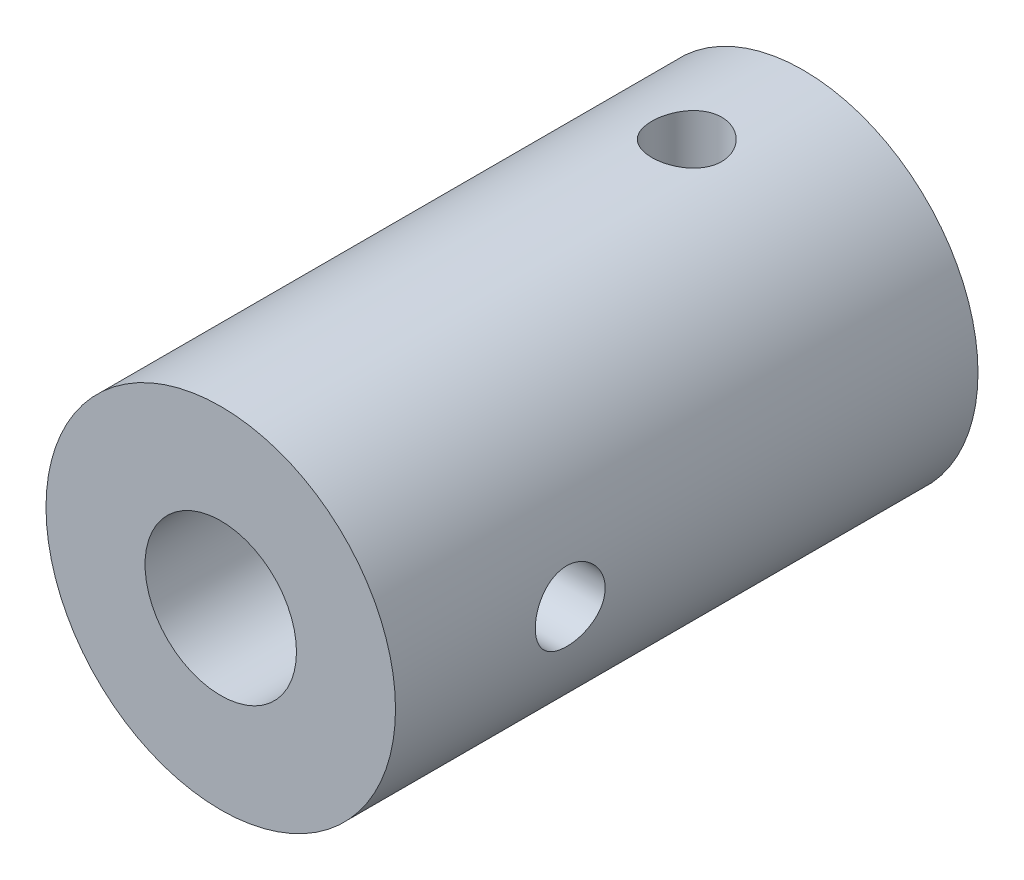
SolidWorks part; units mm, degrees
ref_plane "Front Plane" through (0, 0, 0) normal (0, 0, 1) x (1, 0, 0)
ref_plane "Top Plane" through (0, 0, 0) normal (0, 1, 0) x (1, 0, 0)
ref_plane "Right Plane" through (0, 0, 0) normal (1, 0, 0) x (0, 0, -1)
sketch "Sketch3" plane through (0, 0, 0) normal (0, 0, 1) x (1, 0, 0)
  circle A0 centre (0, 0) radius 7.5
  circle A1 centre (0, 0) radius 3.25
  dimension "D1" = 6.5
  dimension "D2" = 15
extrude "Boss-Extrude1" add sketch "Sketch3" along normal mid plane 25
sketch "Sketch4" plane through (0, 0, 0) normal (1, 0, 0) x (0, 0, -1)
  line L0 (-12.5, 7.5) -> (-12.5, -7.5) construction
  line L1 (12.5, -7.5) -> (12.5, 7.5) construction
  line L2 (-12.5, 7.5) -> (-12.5, -7.5)
  line L3 (12.5, -7.5) -> (12.5, 7.5)
  line L4 (12.5, 0) -> (-12.5, 0) construction
  circle A0 centre (-5, 0) radius 1.5
  dimension "D2" = 3
  dimension "D1" = 5
extrude "Cut-Extrude1" cut sketch "Sketch4" against normal through all both and the other way through all contours A0
sketch "Sketch5" plane through (0, 0, 0) normal (0, 1, 0) x (1, 0, 0)
  line L0 (0, 0) -> (0, 12.5) construction
  line L1 (7.5, 12.5) -> (-7.5, 12.5) construction
  circle A0 centre (0, 7.5) radius 1.5
  dimension "D2" = 3
  dimension "D1" = 5
extrude "Cut-Extrude2" cut sketch "Sketch5" against normal through all both and the other way through all
